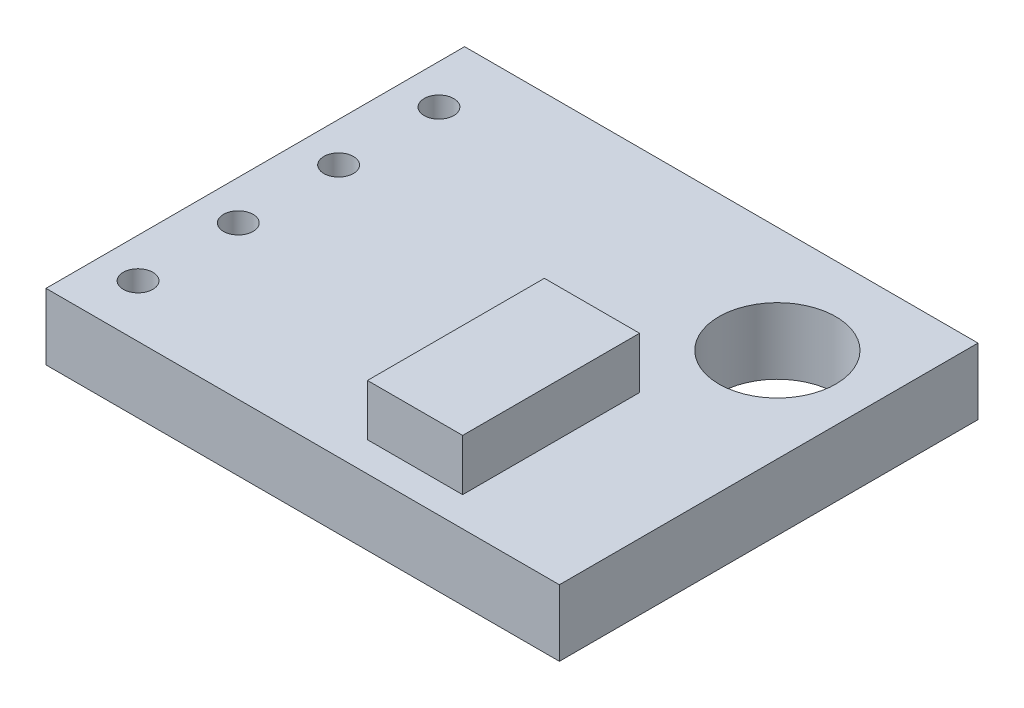
SolidWorks part; units mm, degrees
ref_plane "Alzado" through (0, 0, 0) normal (0, 0, 1) x (1, 0, 0)
ref_plane "Planta" through (0, 0, 0) normal (0, 1, 0) x (1, 0, 0)
ref_plane "Vista lateral" through (0, 0, 0) normal (1, 0, 0) x (0, 0, -1)
sketch "Croquis1" plane through (0, 0, 0) normal (0, 1, 0) x (1, 0, 0)
  line L1 (-6.5, 5.3) -> (6.5, 5.3)
  line L2 (-6.5, 5.3) -> (-6.5, -5.3)
  line L3 (-6.5, -5.3) -> (6.5, -5.3)
  line L4 (6.5, 5.3) -> (6.5, -5.3)
  line L5 (-6.5, 5.3) -> (6.5, -5.3) construction
  line L6 (-6.5, -5.3) -> (6.5, 5.3) construction
  point P0 (0, 0)
  dimension "D1" = 10.6
  dimension "D2" = 13
extrude "Saliente-Extruir1" add sketch "Croquis1" along normal blind 1.68
sketch "Croquis2" plane through (0, 1.68, 0) normal (0, 1, 0) x (1, 0, 0)
  line L0 (-6.5, -5.3) -> (6.5, -5.3) construction
  line L1 (0.89, -0.07) -> (3.3, -0.07)
  line L2 (0.89, -0.07) -> (0.89, -4.55)
  line L3 (0.89, -4.55) -> (3.3, -4.55)
  line L4 (3.3, -0.07) -> (3.3, -4.55)
  line L5 (0.89, -0.07) -> (3.3, -4.55) construction
  line L6 (0.89, -4.55) -> (3.3, -0.07) construction
  line L7 (6.5, -5.3) -> (6.5, 5.3) construction
  point P0 (2.095, -2.31)
  dimension "D1" = 2.41
  dimension "D2" = 4.48
  dimension "D3" = 5.23
  dimension "D4" = 5.61
extrude "Saliente-Extruir2" add sketch "Croquis2" along normal blind 1.3
sketch "Croquis3" plane through (0, 1.68, 0) normal (0, 1, 0) x (1, 0, 0)
  line L0 (6.5, -5.3) -> (6.5, 5.3) construction
  line L1 (6.5, 5.3) -> (-6.5, 5.3) construction
  circle A0 centre (4.12, 2.6) radius 1.48
  dimension "D1" = 2.96
  dimension "D2" = 2.38
  dimension "D3" = 2.7
extrude "Cortar-Extruir1" cut sketch "Croquis3" against normal through all
sketch "Croquis4" plane through (0, 1.68, 0) normal (0, 1, 0) x (1, 0, 0)
  line L0 (-6.5, 5.3) -> (-6.5, -5.3) construction
  line L1 (6.5, 5.3) -> (-6.5, 5.3) construction
  circle A0 centre (-5.5, 3.65) radius 0.375
  circle A1 centre (-5.5, 1.11) radius 0.375
  circle A2 centre (-5.5, -1.43) radius 0.375
  circle A3 centre (-5.5, -3.97) radius 0.375
  dimension "D1" = 0.75
  dimension "D2" = 1
  dimension "D3" = 1.65
  dimension "D4" = 4
extrude "Cortar-Extruir2" cut sketch "Croquis4" against normal through all
